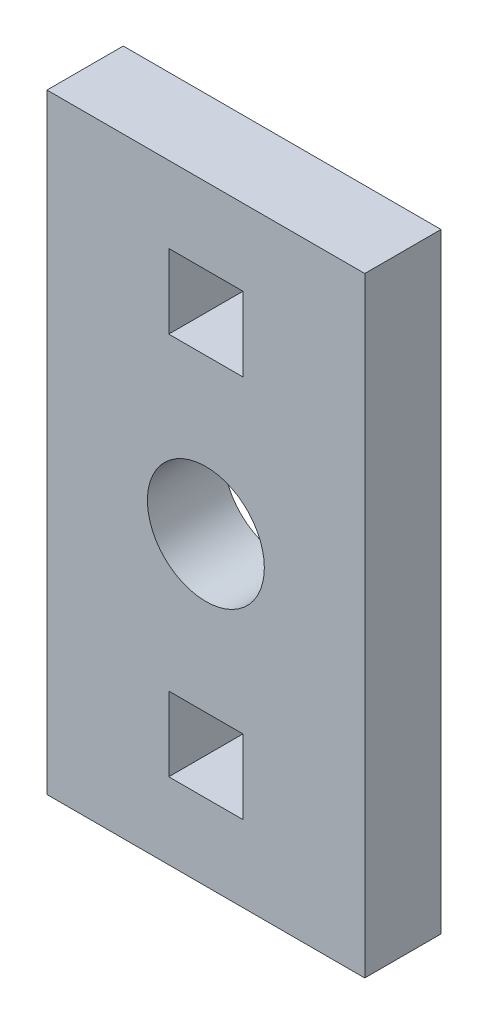
SolidWorks part; units mm, degrees
ref_plane "Front Plane" through (0, 0, 0) normal (0, 0, 1) x (1, 0, 0)
ref_plane "Top Plane" through (0, 0, 0) normal (0, 1, 0) x (1, 0, 0)
ref_plane "Right Plane" through (0, 0, 0) normal (1, 0, 0) x (0, 0, -1)
sketch "Sketch1" plane through (0, 0, 0) normal (0, 0, 1) x (1, 0, 0)
  line L0 (-11.8033, -4.0956) -> (4.1694, -4.0956) construction
  line L1 (-10.4167, 7.9044) -> (2.0833, 7.9044)
  line L2 (-10.4167, 7.9044) -> (-10.4167, -16.0956)
  line L3 (-10.4167, -16.0956) -> (2.0833, -16.0956)
  line L4 (2.0833, 7.9044) -> (2.0833, -16.0956)
  line L5 (-5.6267, 4.9044) -> (-2.7067, 4.9044)
  line L6 (-5.6267, 4.9044) -> (-5.6267, 1.9844)
  line L7 (-5.6267, 1.9844) -> (-2.7067, 1.9844)
  line L8 (-2.7067, 4.9044) -> (-2.7067, 1.9844)
  line L9 (-2.7067, -13.0956) -> (-2.7067, -10.1756)
  line L10 (-5.6267, -10.1756) -> (-2.7067, -10.1756)
  line L11 (-5.6267, -13.0956) -> (-5.6267, -10.1756)
  line L12 (-5.6267, -13.0956) -> (-2.7067, -13.0956)
  circle A0 centre (-4.1667, -4.0956) radius 2.3
  dimension "D3" = 4.6
  dimension "D4" = 12
  dimension "D5" = 6.25
  dimension "D1" = 12.5
  dimension "D2" = 24
  dimension "D6" = 2.92
  dimension "D7" = 2.92
  dimension "D8" = 3
  dimension "D9" = 4.79
extrude "Boss-Extrude1" add sketch "Sketch1" along normal blind 3
